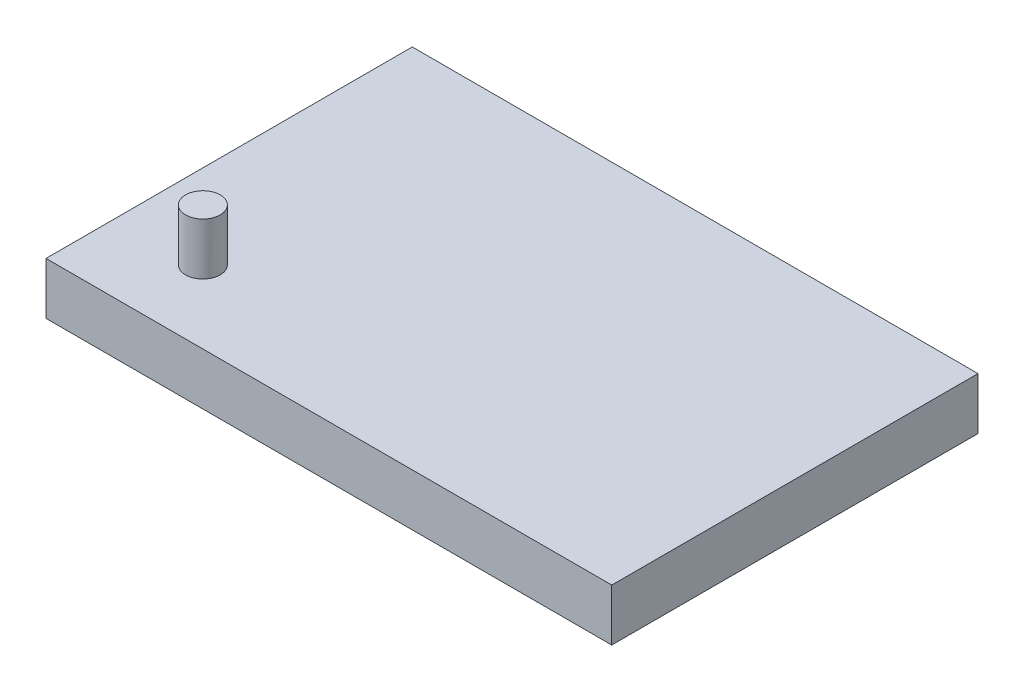
SolidWorks part; units mm, degrees
ref_plane "Front Plane" through (0, 0, 0) normal (0, 0, 1) x (1, 0, 0)
ref_plane "Top Plane" through (0, 0, 0) normal (0, 1, 0) x (1, 0, 0)
ref_plane "Right Plane" through (0, 0, 0) normal (1, 0, 0) x (0, 0, -1)
sketch "Sketch4" plane through (0, 0, 0) normal (0, 1, 0) x (1, 0, 0)
  line L1 (-81.6251, -52.8431) -> (81.6251, -52.8431)
  line L2 (-81.6251, -52.8431) -> (-81.6251, 52.8431)
  line L3 (-81.6251, 52.8431) -> (81.6251, 52.8431)
  line L4 (81.6251, -52.8431) -> (81.6251, 52.8431)
  line L5 (-81.6251, -52.8431) -> (81.6251, 52.8431) construction
  line L6 (-81.6251, 52.8431) -> (81.6251, -52.8431) construction
  point P0 (0, 0)
extrude "Boss-Extrude2" add sketch "Sketch4" along normal blind 15
sketch "Sketch5" plane through (0, 15, 0) normal (0, 1, 0) x (1, 0, 0)
  circle A0 centre (-57.3687, -31.833) radius 5
  dimension "D1" = 10
extrude "Boss-Extrude3" add sketch "Sketch5" along normal blind 15
sketch "Sketch6" plane through (0, 15, 0) normal (0, 1, 0) x (1, 0, 0)
  spline S0 degree 3 poles (-31.973, -31.612) (-1.018, -43.1853) (-1.5819, 12.7883) (72.6875, 15.2237) (42.286, 42.0718) knots 0 0 0 0 0.472212 1 1 1 1
